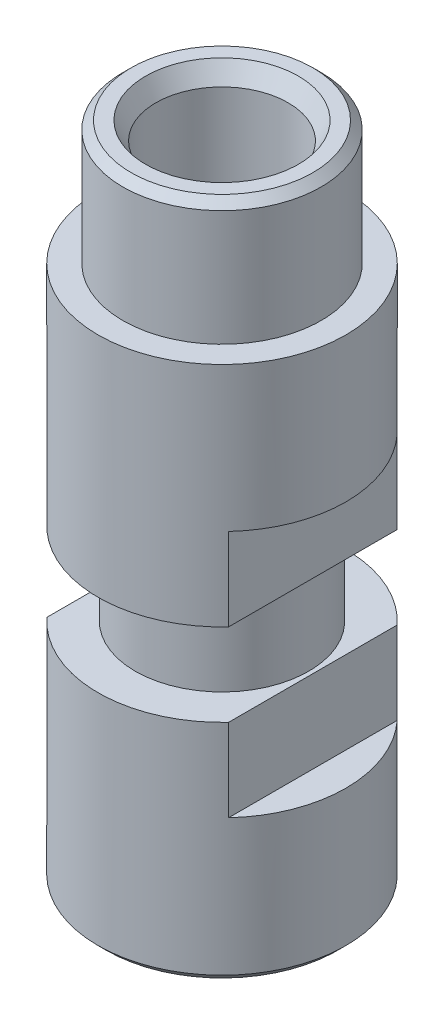
SolidWorks part; units mm, degrees
ref_plane "Front Plane" through (0, 0, 0) normal (0, 0, 1) x (1, 0, 0)
ref_plane "Top Plane" through (0, 0, 0) normal (0, 1, 0) x (1, 0, 0)
ref_plane "Right Plane" through (0, 0, 0) normal (1, 0, 0) x (0, 0, -1)
sketch "Sketch1" plane through (0, 0, 0) normal (0, 1, 0) x (1, 0, 0)
  circle A0 centre (0, 0) radius 3
  dimension "D1" = 6
extrude "Boss-Extrude1" [suppressed] add sketch "Sketch1" along normal blind 7
cosmetic thread "Rosca cosmética1" [suppressed] parameters "D2"=5
sketch "Sketch2" [suppressed] plane through (0, 7, 0) normal (0, 1, 0) x (1, 0, 0)
  circle A0 centre (0, 0) radius 2.1
  dimension "D1" = 4.2
extrude "Boss-Extrude2" [suppressed] add sketch "Sketch2" along normal blind 2
sketch "Sketch3" [suppressed] plane through (0, 9, 0) normal (0, 1, 0) x (1, 0, 0)
  circle A0 centre (0, 0) radius 3
  dimension "D1" = 6
extrude "Boss-Extrude3" [suppressed] add sketch "Sketch3" along normal blind 6
cosmetic thread "Rosca cosmética2" parameters "D2"=5
sketch "Sketch4" [suppressed] plane through (0, 15, 0) normal (0, 1, 0) x (1, 0, 0)
  circle A0 centre (0, 0) radius 1.6
  dimension "D1" = 3.2
extrude "Cut-Extrude1" [suppressed] cut sketch "Sketch4" against normal through all
sketch "Croquis1" [suppressed] plane through (0, 15, 0) normal (0, 1, 0) x (1, 0, 0)
  circle A0 centre (0, 0) radius 2.4
  circle A1 centre (0, 0) radius 1.6
  circle A2 centre (0, 0) radius 1.6 construction
  dimension "D1" = 4.8
extrude "Saliente-Extruir1" [suppressed] add sketch "Croquis1" along normal blind 3
chamfer "Chaflán1" [suppressed] distance 0.2 angle 45
chamfer "Chaflán2" [suppressed] distance 0.2 angle 45
chamfer "Chaflán3" [suppressed] distance 0.25 angle 60
sketch "Croquis2" [suppressed] plane through (0, 0, 0) normal (0, 0, 1) x (1, 0, 0)
  line L0 (0, 17.8) -> (0, 0) construction
  line L1 (3, 11) -> (2.2, 11)
  line L2 (3, 11) -> (3, 5)
  line L3 (3, 5) -> (2.2, 5)
  line L4 (2.2, 11) -> (2.2, 5)
  line L5 (-3, 11) -> (-2.2, 11)
  line L6 (-3, 11) -> (-3, 5)
  line L7 (-3, 5) -> (-2.2, 5)
  line L8 (-2.2, 11) -> (-2.2, 5)
  line L9 (-2.4, 17.8) -> (2.4, 17.8) construction
  line L10 (-2.1, 8) -> (2.1, 8) construction
  line L11 (-2.1, 9) -> (-2.1, 7) construction
  line L12 (2.1, 7) -> (2.1, 9) construction
  line L13 (-3, 15) -> (-3, 9) construction
  line L14 (3, 9) -> (3, 15) construction
  dimension "D1" = 4.4
  dimension "D2" = 2.2
  dimension "D3" = 6
  dimension "D4" = 3
extrude "Cortar-Extruir1" [suppressed] cut sketch "Croquis2" against normal through all and the other way through all
sketch "Croquis3" plane through (0, 0, 0) normal (0, 0, 1) x (1, 0, 0)
  line L0 (-1.6, 0) -> (-1.6, 16)
  line L1 (-1.6, 16) -> (-2.4, 16)
  line L2 (-2.4, 16) -> (-2.4, 13)
  line L3 (-2.4, 13) -> (-3, 13)
  line L4 (-3, 13) -> (-3, 7.5)
  line L5 (-3, 7.5) -> (-2.1, 7.5)
  line L6 (-2.1, 7.5) -> (-2.1, 5.5)
  line L7 (-2.1, 5.5) -> (-3, 5.5)
  line L8 (-3, 5.5) -> (-3, 0)
  line L9 (-3, 0) -> (-1.6, 0)
  line L10 (0, 0) -> (0, 18.5179) construction
  dimension "D1" = 3.2
  dimension "D2" = 6
  dimension "D3" = 4.8
  dimension "D4" = 16
  dimension "D5" = 2
  dimension "D6" = 3
  dimension "D7" = 5.5
  dimension "D8" = 4.2
revolve "Revolución1" add sketch "Croquis3" angle 360 about L10
cosmetic thread "Rosca cosmética3" parameters "D2"=4.891
cosmetic thread "Rosca cosmética4" parameters "D2"=4.891
chamfer "Chaflán4" distance 0.2 angle 45 2 edges at (0, 16, -2.4) (0, 0, -3)
chamfer "Chaflán5" distance 0.25 angle 60 1 edges at (0, 16, -1.6)
sketch "Croquis4" plane through (0, 0, 0) normal (0, 0, 1) x (1, 0, 0)
  line L0 (0, 0) -> (0, 16) construction
  line L1 (-3, 9.5) -> (-2.2, 9.5)
  line L2 (-3, 9.5) -> (-3, 3.5)
  line L3 (-3, 3.5) -> (-2.2, 3.5)
  line L4 (-2.2, 9.5) -> (-2.2, 3.5)
  line L5 (2.2, 9.5) -> (3, 9.5)
  line L6 (2.2, 9.5) -> (2.2, 3.5)
  line L7 (2.2, 3.5) -> (3, 3.5)
  line L8 (3, 9.5) -> (3, 3.5)
  line L9 (-2.8, 0) -> (2.8, 0) construction
  line L10 (2.2, 16) -> (-2.2, 16) construction
  line L11 (3, 7.5) -> (3, 5.5) construction
  line L12 (3, 6.5) -> (2.2, 6.5) construction
  dimension "D1" = 6
  dimension "D2" = 4.4
extrude "Cortar-Extruir2" cut sketch "Croquis4" against normal through all and the other way through all
equation "\"D2@Croquis2\"=\"D1@Croquis2\"/2"
equation "\"D4@Croquis2\"=\"D3@Croquis2\"/2"
